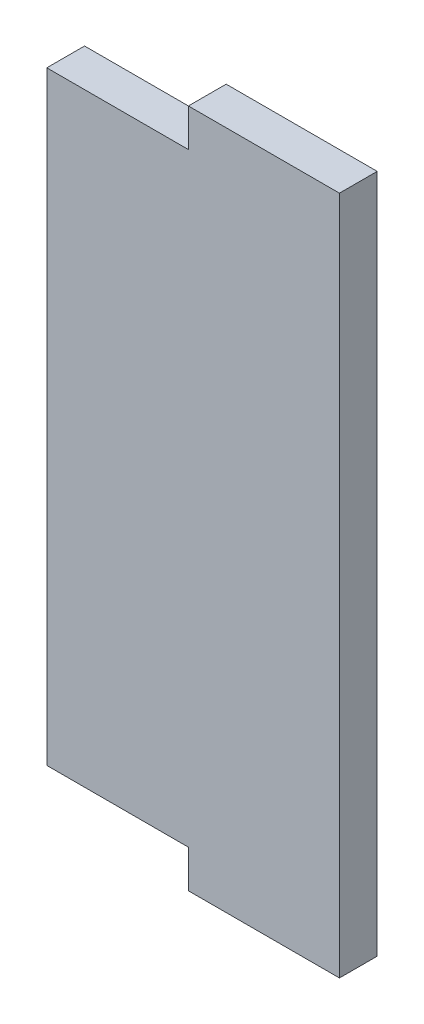
SolidWorks part; units mm, degrees
ref_plane "Front Plane" through (0, 0, 0) normal (0, 0, 1) x (1, 0, 0)
ref_plane "Top Plane" through (0, 0, 0) normal (0, 1, 0) x (1, 0, 0)
ref_plane "Right Plane" through (0, 0, 0) normal (1, 0, 0) x (0, 0, -1)
sketch "Sketch1" plane through (0, 0, 0) normal (0, 0, 1) x (1, 0, 0)
  line L0 (60.325, 50.8) -> (47.625, 50.8) construction
  line L1 (60.325, -3.175) -> (47.625, -3.175)
  line L2 (60.325, -3.175) -> (60.325, 53.975)
  line L3 (60.325, 53.975) -> (47.625, 53.975)
  line L4 (35.7188, 0) -> (35.7188, 50.8)
  line L7 (35.7188, 50.8) -> (47.625, 50.8)
  line L8 (47.625, 53.975) -> (47.625, 50.8)
  line L10 (47.625, 0) -> (35.7188, 0)
  line L11 (47.625, 0) -> (47.625, -3.175)
extrude "Boss-Extrude1" add sketch "Sketch1" along normal blind 3.175 contours L2 L3 L8 L7 L4 L10 L11 L1
